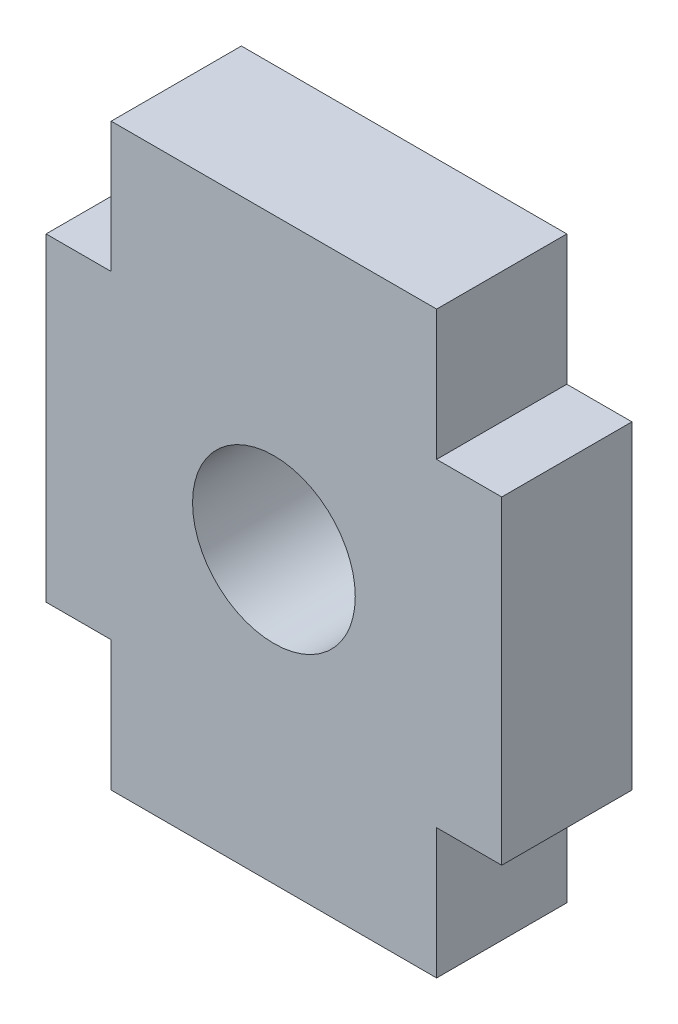
SolidWorks part; units mm, degrees
ref_plane "Front Plane" through (0, 0, 0) normal (0, 0, 1) x (1, 0, 0)
ref_plane "Top Plane" through (0, 0, 0) normal (0, 1, 0) x (1, 0, 0)
ref_plane "Right Plane" through (0, 0, 0) normal (1, 0, 0) x (0, 0, -1)
sketch "Sketch1" plane through (0, 0, 0) normal (0, 0, 1) x (1, 0, 0)
  line L0 (1952.1768, 1465.7841) -> (1957.1768, 1465.7841)
  line L1 (1952.1768, 1456.8841) -> (1957.1768, 1456.8841)
  line L3 (1957.1768, 1458.8841) -> (1957.1768, 1456.8841)
  line L4 (1957.1768, 1458.8841) -> (1958.1768, 1458.8841)
  line L5 (1958.1768, 1463.7841) -> (1958.1768, 1458.8841)
  line L6 (1957.1768, 1463.7841) -> (1957.1768, 1465.7841)
  line L7 (1957.1768, 1463.7841) -> (1958.1768, 1463.7841)
  line L37 (1952.1768, 1458.8841) -> (1951.1768, 1458.8841)
  line L40 (1952.1768, 1458.8841) -> (1952.1768, 1456.8841)
  line L127 (1952.1768, 1463.7841) -> (1951.1768, 1463.7841)
  line L130 (1952.1768, 1463.7841) -> (1952.1768, 1465.7841)
  line L131 (1951.1768, 1463.7841) -> (1951.1768, 1458.8841)
  circle A82 centre (1954.6768, 1461.3341) radius 1.25
  dimension "D5" = 2.5
  dimension "D1" = 4.9
  dimension "D2" = 1
  dimension "D3" = 5
  dimension "D4" = 1
  dimension "D7" = 8.9
extrude "Boss-Extrude1" add sketch "Sketch1" along normal blind 2
